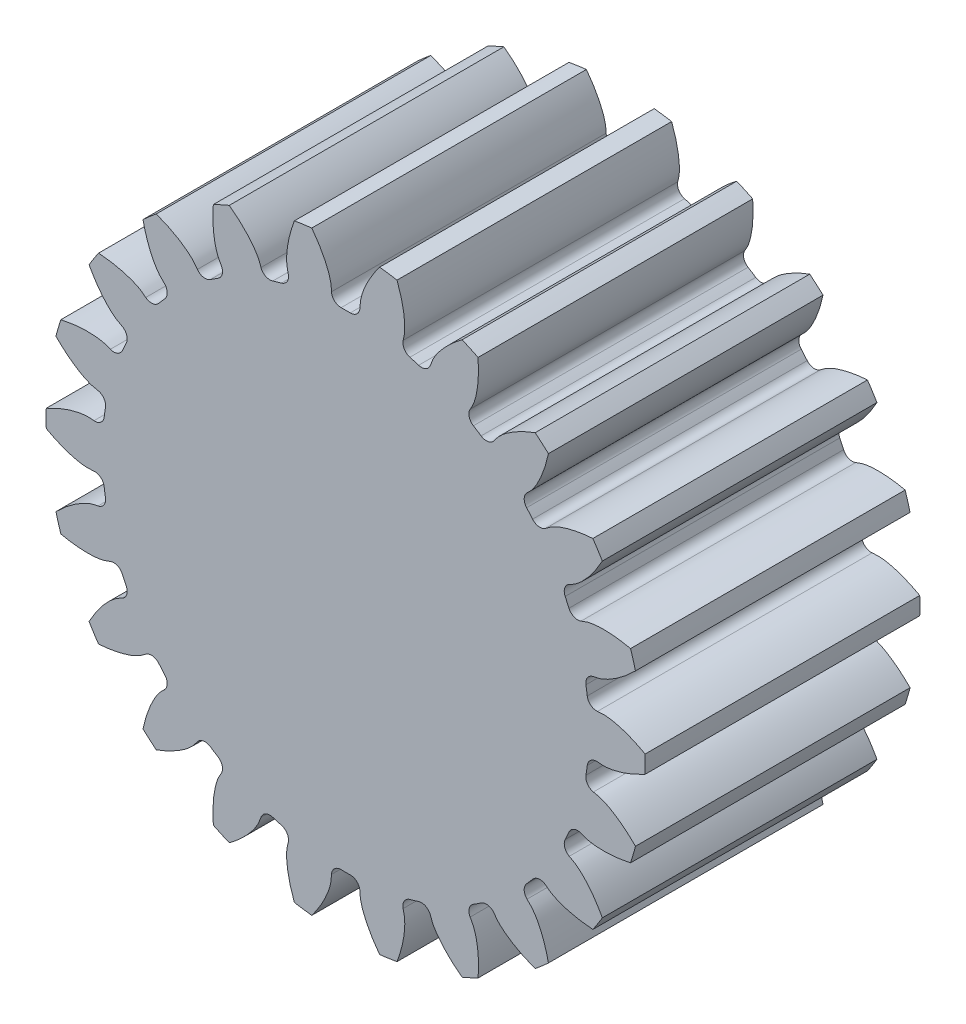
SolidWorks part; units mm, degrees
ref_plane "前视基准面" through (0, 0, 0) normal (0, 0, 1) x (1, 0, 0)
ref_plane "上视基准面" through (0, 0, 0) normal (0, 1, 0) x (1, 0, 0)
ref_plane "右视基准面" through (0, 0, 0) normal (1, 0, 0) x (0, 0, -1)
other "Configuration Table"
ref_axis "Axis1" through (0, 0, -88.99) along (0, 0, 1)
sketch "草图1" plane through (0, 0, 0) normal (0, 0, 1) x (1, 0, 0)
  circle A0 centre (0, 0) radius 12
extrude "LaShenA" add sketch "草图1" along normal blind 11
sketch "SketchA" plane through (0, 0, 11) normal (0, 0, 1) x (1, 0, 0)
  line L0 (0, 0) -> (0, 12) construction
  arc A0 (0.1829, 9.7483) -> (-0.1829, 9.7483) centre (0, 0) ccw
  arc A1 (1.7922, 12.4394) -> (-1.7922, 12.4394) centre (0, 0) ccw
  arc A2 (-0.1829, 9.7483) -> (-0.5693, 10.1058) centre (-0.19, 10.1282) cw
  arc A3 (0.5693, 10.1058) -> (0.1829, 9.7483) centre (0.19, 10.1282) cw
  circle A4 centre (0, 0) radius 10.3366 construction
  circle A5 centre (0, 0) radius 12 construction
  circle A6 centre (0, 0) radius 9.75 construction
  circle A7 centre (0, 0) radius 11 construction
  spline S0 degree 3 poles (0.5693, 10.1058) (0.5736, 10.1777) (0.5776, 10.2793) (0.5937, 10.3939) (0.606, 10.4523) (0.6168, 10.4986) (0.6308, 10.5517) (0.6482, 10.6114) (0.6693, 10.6775) (0.6947, 10.75) (0.7246, 10.8287) (0.7593, 10.9132) (0.7992, 11.0036) (0.8447, 11.0994) (0.8959, 11.2005) (0.9533, 11.3067) (1.0172, 11.4176) (1.0878, 11.533) (1.1655, 11.6527) (1.2504, 11.7762) (1.3429, 11.9034) (1.4432, 12.0339) (1.5907, 12.2156) (1.7093, 12.3501) (1.7922, 12.4394) knots 0.122554 0.122554 0.122554 0.122554 0.192705 0.222547 0.235684 0.251209 0.269123 0.289425 0.312116 0.337195 0.364662 0.394518 0.426763 0.461396 0.498418 0.537828 0.579626 0.623813 0.670389 0.719353 0.770705 0.824446 0.880576 1 1 1 1
  spline S1 degree 3 poles (-0.5693, 10.1058) (-0.5736, 10.1777) (-0.5776, 10.2793) (-0.5937, 10.3939) (-0.606, 10.4523) (-0.6168, 10.4986) (-0.6308, 10.5517) (-0.6482, 10.6114) (-0.6693, 10.6775) (-0.6947, 10.75) (-0.7246, 10.8287) (-0.7593, 10.9132) (-0.7992, 11.0036) (-0.8447, 11.0994) (-0.8959, 11.2005) (-0.9533, 11.3067) (-1.0172, 11.4176) (-1.0878, 11.533) (-1.1655, 11.6527) (-1.2504, 11.7762) (-1.3429, 11.9034) (-1.4432, 12.0339) (-1.5907, 12.2156) (-1.7093, 12.3501) (-1.7922, 12.4394) knots 0.122554 0.122554 0.122554 0.122554 0.192705 0.222547 0.235684 0.251209 0.269123 0.289425 0.312116 0.337195 0.364662 0.394518 0.426763 0.461396 0.498418 0.537828 0.579626 0.623813 0.670389 0.719353 0.770705 0.824446 0.880576 1 1 1 1
  dimension "D1" = 0.38
  dimension "Db" = 20.6732
  dimension "Da" = 24
  dimension "Df" = 19.5
  dimension "Dn" = 22
extrude "Cut-ExtrudeA" cut sketch "SketchA" against normal blind 11
pattern_circular "www.KYTool.cn" count 22 over 360 about axis through (0, 0, -88.99) along (0, 0, 1) of "Cut-ExtrudeA"
